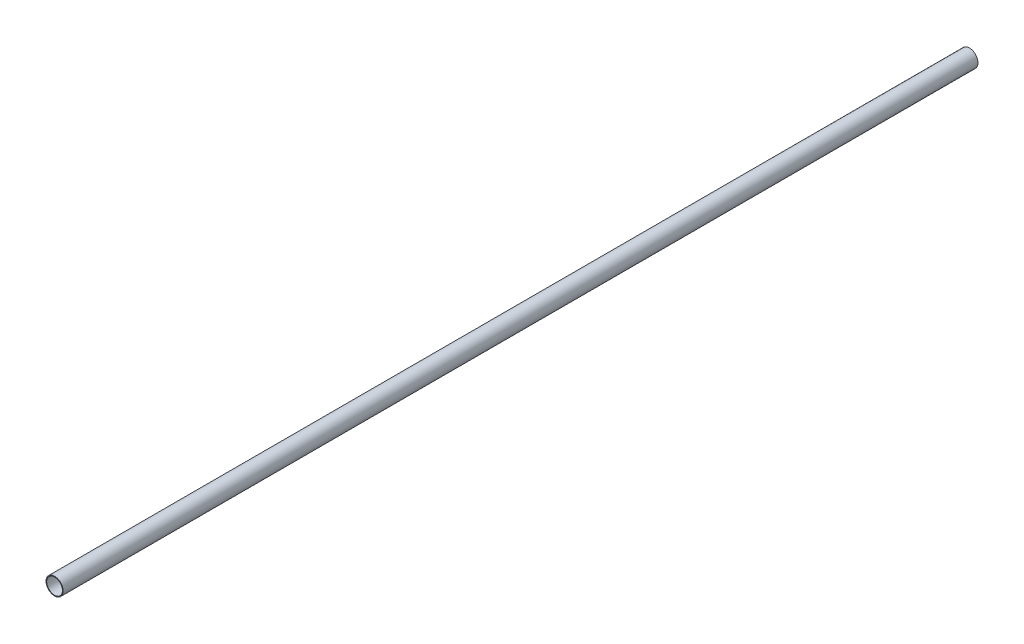
SolidWorks part; units mm, degrees
ref_plane "Front Plane" through (0, 0, 0) normal (0, 0, 1) x (1, 0, 0)
ref_plane "Top Plane" through (0, 0, 0) normal (0, 1, 0) x (1, 0, 0)
ref_plane "Right Plane" through (0, 0, 0) normal (1, 0, 0) x (0, 0, -1)
sketch "Sketch1" plane through (0, 0, 0) normal (0, 0, 1) x (1, 0, 0)
  circle A0 centre (0, 0) radius 6.9
  circle A1 centre (0, 0) radius 7.5
  dimension "D1" = 15
  dimension "D2" = 13.8
extrude "Boss-Extrude1" add sketch "Sketch1" along normal blind 800
